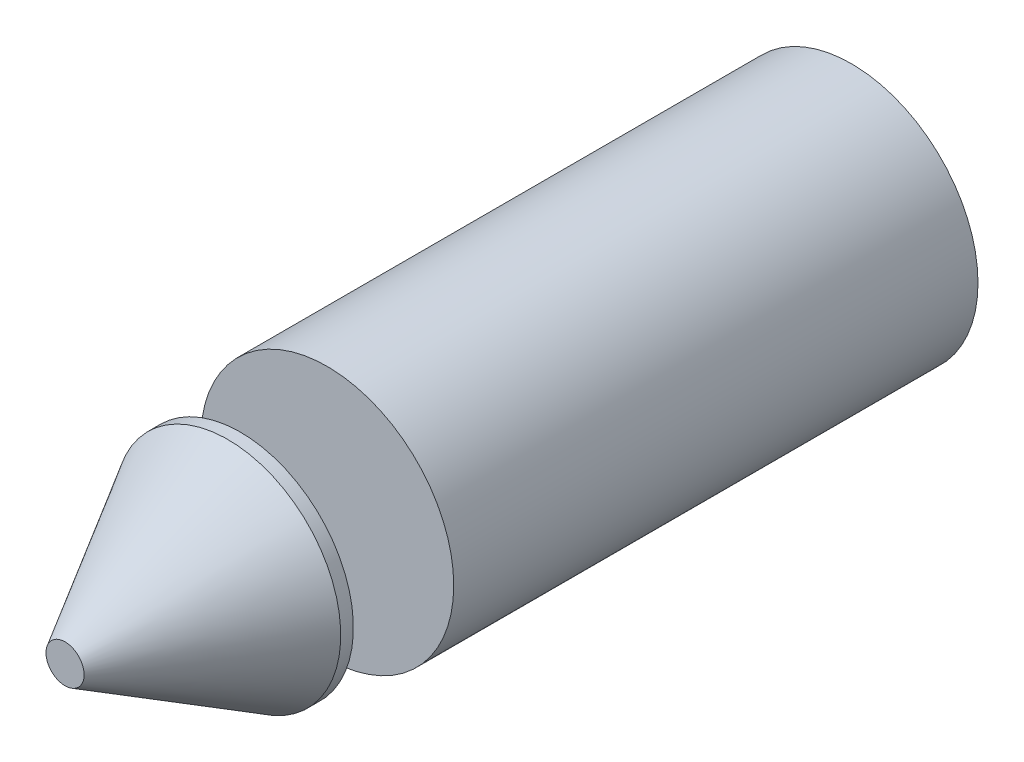
SolidWorks part; units mm, degrees
ref_plane "Front Plane" through (0, 0, 0) normal (0, 0, 1) x (1, 0, 0)
ref_plane "Top Plane" through (0, 0, 0) normal (0, 1, 0) x (1, 0, 0)
ref_plane "Right Plane" through (0, 0, 0) normal (1, 0, 0) x (0, 0, -1)
sketch "Sketch1" plane through (0, 0, 0) normal (0, 0, 1) x (1, 0, 0)
  circle A0 centre (0, 0) radius 17.78
  dimension "D1" = 35.56
extrude "Boss-Extrude1" add sketch "Sketch1" along normal blind 73.66
ref_plane "Plane1" through (0, 0, 85.852) normal (0, 0, 1) x (1, 0, 0)
sketch "Sketch2" plane through (0, 0, 85.852) normal (0, 0, 1) x (1, 0, 0)
  circle A0 centre (0, 0) radius 17.78 construction
  circle A1 centre (0, 0) radius 17.78 construction
  circle A2 centre (0, 0) radius 15.875
  dimension "D1" = 31.75
extrude "Boss-Extrude2" add sketch "Sketch2" along normal blind 24.638 separate body
chamfer "Chamfer1" distance 22.86 angle 30 1 edges at (15.875, 0, 110.49)
